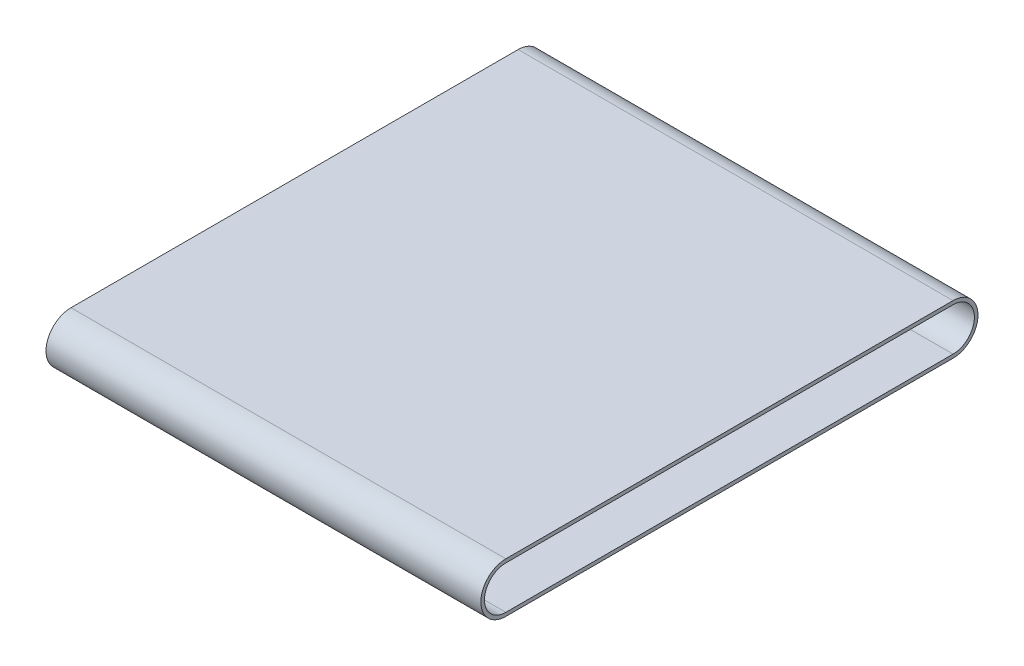
SolidWorks part; units mm, degrees
material "Rubber"
ref_plane "Front Plane" through (0, 0, 0) normal (0, 0, 1) x (1, 0, 0)
ref_plane "Top Plane" through (0, 0, 0) normal (0, 1, 0) x (1, 0, 0)
ref_plane "Right Plane" through (0, 0, 0) normal (1, 0, 0) x (0, 0, -1)
sketch "Sketch1" plane through (0, 0, 0) normal (1, 0, 0) x (0, 0, -1)
  line L0 (0, 25.527) -> (457.073, 25.527)
  line L1 (0, 21.844) -> (457.073, 21.844)
  line L2 (0, -21.844) -> (457.073, -21.844)
  line L3 (0, -25.527) -> (457.073, -25.527)
  arc A0 (0, 21.844) -> (0, -21.844) centre (0, 0) ccw
  arc A1 (0, 25.527) -> (0, -25.527) centre (0, 0) ccw
  arc A2 (457.073, -25.527) -> (457.073, 25.527) centre (457.073, 0) ccw
  arc A3 (457.073, -21.844) -> (457.073, 21.844) centre (457.073, 0) ccw
  dimension "D1" = 21.844
  dimension "D2" = 3.683
  dimension "D3" = 457.073
extrude "Boss-Extrude1" add sketch "Sketch1" along normal blind 444.5
